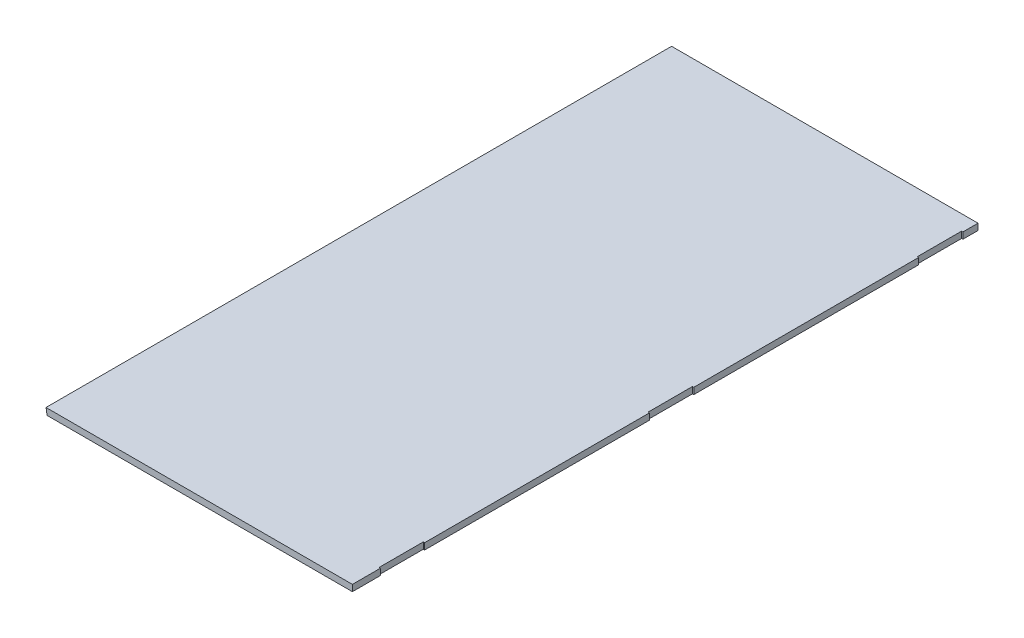
SolidWorks part; units mm, degrees
material "Plywood"
ref_plane "Front Plane" through (0, 0, 0) normal (0, 0, 1) x (1, 0, 0)
ref_plane "Top Plane" through (0, 0, 0) normal (0, 1, 0) x (1, 0, 0)
ref_plane "Right Plane" through (0, 0, 0) normal (1, 0, 0) x (0, 0, -1)
sketch "Sketch1" plane through (0, 0, 0) normal (0, 1, 0) x (1, 0, 0)
  line L1 (-438.912, -896.112) -> (438.912, -896.112)
  line L2 (-438.912, -896.112) -> (-438.912, 896.112)
  line L3 (-438.912, 896.112) -> (438.912, 896.112)
  line L4 (438.912, -896.112) -> (438.912, 896.112)
  line L5 (-438.912, -896.112) -> (438.912, 896.112) construction
  line L6 (-438.912, 896.112) -> (438.912, -896.112) construction
  point P0 (0, 0)
  dimension "D1" = 1792.224
  dimension "D2" = 877.824
extrude "Boss-Extrude1" add sketch "Sketch1" along normal blind 18.2562
sketch "Sketch2" plane through (438.912, 0, 0) normal (1, 0, 0) x (0, 0, -1)
  line L0 (-816.356, 18.2562) -> (-816.356, 0)
  line L1 (-896.112, 18.2562) -> (896.112, 18.2562) construction
  line L2 (-896.112, 0) -> (896.112, 0) construction
  line L3 (-816.356, 0) -> (-689.356, 0)
  line L4 (-689.356, 0) -> (-689.356, 18.2562)
  line L5 (-689.356, 18.2562) -> (-816.356, 18.2562)
  line L6 (-816.356, 9.1281) -> (-896.112, 9.1281) construction
  line L7 (-896.112, 18.2562) -> (-896.112, 0) construction
  line L8 (81.788, 18.2562) -> (-45.212, 18.2562)
  line L9 (-45.212, 18.2562) -> (-45.212, 0)
  line L10 (-45.212, 0) -> (81.788, 0)
  line L11 (81.788, 0) -> (81.788, 18.2562)
  line L12 (852.932, 18.2562) -> (725.932, 18.2563)
  line L13 (725.932, 18.2563) -> (725.932, 0)
  line L14 (725.932, 0) -> (852.932, 0)
  line L15 (852.932, 0) -> (852.932, 18.2562)
  line L16 (852.932, 9.1281) -> (896.112, 9.1281) construction
  line L18 (-689.356, 9.1281) -> (-45.212, 9.1281) construction
  line L19 (725.932, 9.1281) -> (81.788, 9.1281) construction
  line L20 (896.112, 18.2562) -> (896.112, 0) construction
  dimension "D1" = 127
  dimension "D3" = 79.756
  dimension "D4" = 43.18
  dimension "D2" = 3
extrude "Cut-Extrude1" cut sketch "Sketch2" against normal blind 3.81
ref_plane "Plane1" through (-438.912, 0, 896.112) normal (0, 0, 1) x (1, 0, 0)
sketch "Sketch3" plane through (-438.912, 0, 896.112) normal (0, 0, 1) x (1, 0, 0)
  line L0 (0, 18.2562) -> (3.2191, 0)
  line L1 (0, 0) -> (877.824, 0) construction
  line L2 (3.2191, 0) -> (0, 0)
  line L3 (0, 0) -> (0, 18.2562)
  dimension "D1" = 10
extrude "Cut-Extrude2" cut sketch "Sketch3" against normal blind 7620
